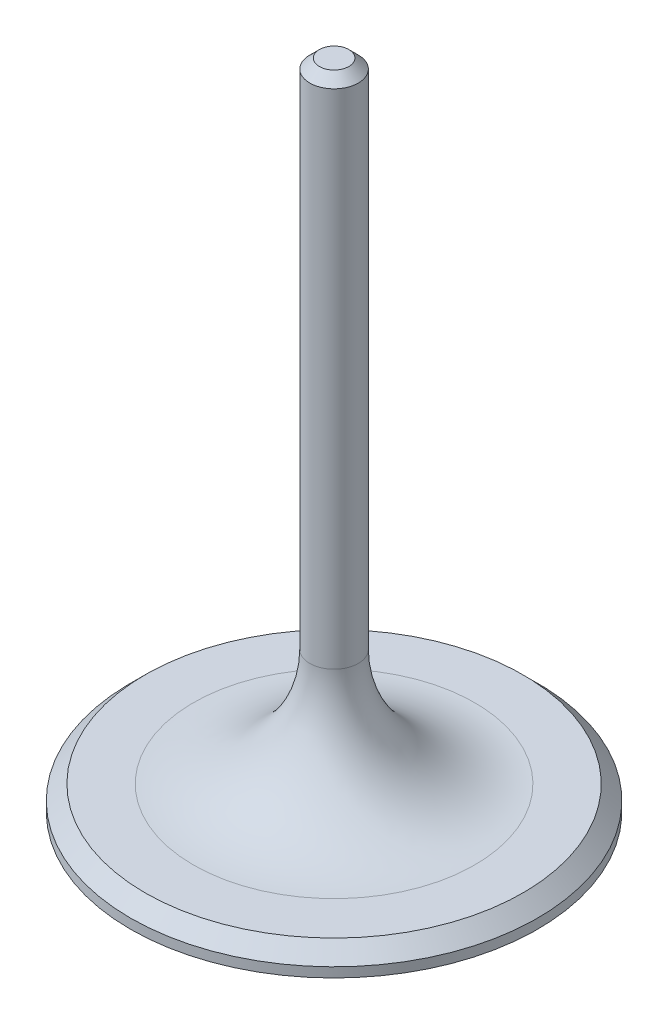
SolidWorks part; units mm, degrees
ref_plane "Front Plane" through (0, 0, 0) normal (0, 0, 1) x (1, 0, 0)
ref_plane "Top Plane" through (0, 0, 0) normal (0, 1, 0) x (1, 0, 0)
ref_plane "Right Plane" through (0, 0, 0) normal (1, 0, 0) x (0, 0, -1)
sketch "Sketch1" plane through (0, 0, 0) normal (0, 0, 1) x (1, 0, 0)
  line L0 (0, 91.8789) -> (0, -11.1703) construction
  line L1 (0, 85.55) -> (3.18, 85.55)
  line L2 (3.18, 85.55) -> (3.18, 18.43)
  line L3 (18.43, 3.18) -> (24.76, 3.18)
  line L4 (24.76, 3.18) -> (26.67, 1.27)
  line L5 (26.67, 1.27) -> (0, 1.27)
  line L6 (0, 1.27) -> (0, 0) construction
  line L7 (0, 0) -> (26.67, 0)
  line L8 (26.67, 0) -> (26.67, 1.27)
  line L9 (0, 85.55) -> (0, 0)
  arc A0 (3.18, 18.43) -> (18.43, 3.18) centre (18.43, 18.43) ccw
  point P12 (7.6466, 7.6466)
  dimension "D6" = 15.25
  dimension "D7" = 26.67
  dimension "D1" = 3.18
  dimension "D2" = 85.55
  dimension "D3" = 3.18
  dimension "D4" = 1.27
  dimension "D5" = 45
revolve "Revolve1" add sketch "Sketch1" angle 360 about L0
chamfer "Chamfer1" distance 1.25 angle 45 1 edges at (0, 85.55, 3.18)
